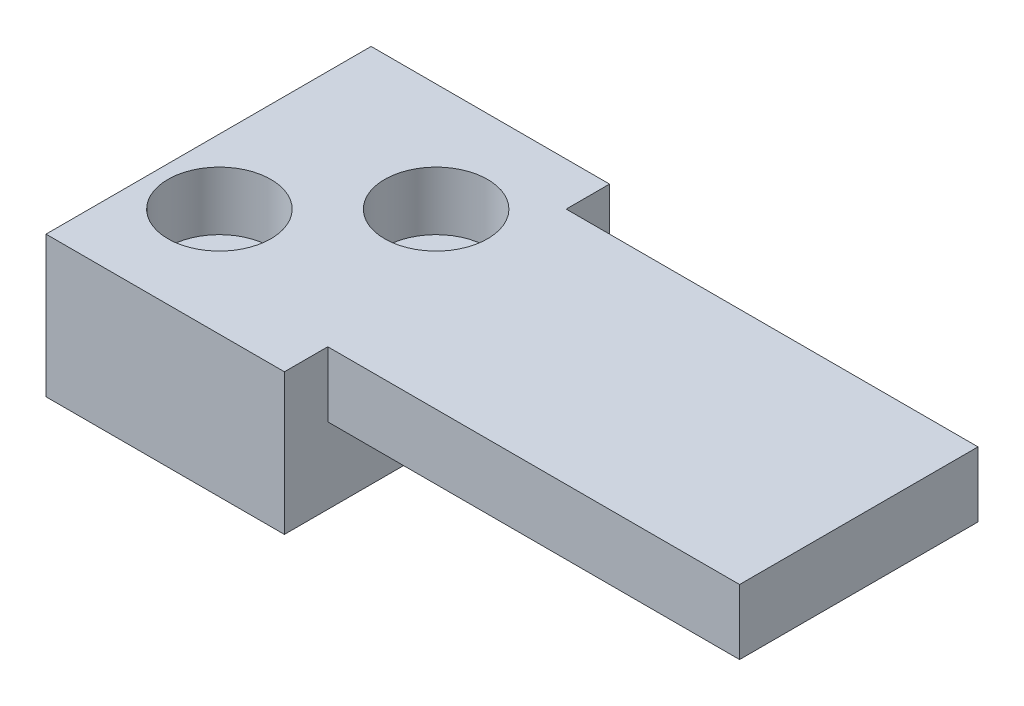
SolidWorks part; units mm, degrees
material "1.7131 (16MnCr5)"
ref_plane "Plano frontal" through (0, 0, 0) normal (0, 0, 1) x (1, 0, 0)
ref_plane "Plano superior" through (0, 0, 0) normal (0, 1, 0) x (1, 0, 0)
ref_plane "Plano direito" through (0, 0, 0) normal (1, 0, 0) x (0, 0, -1)
sketch "Esboço1" plane through (0, 0, 0) normal (0, 0, 1) x (1, 0, 0)
  line L0 (0, 0) -> (60, 0)
  line L1 (0, 0) -> (0, -13)
  line L2 (0, -13) -> (22, -13)
  line L3 (22, -13) -> (22, 0)
  line L4 (60, 0) -> (60, -6)
  line L5 (60, -6) -> (22, -6)
  dimension "D1" = 60
  dimension "D2" = 13
  dimension "D3" = 6
  dimension "D4" = 22
extrude "Ressalto-extrusão1" add sketch "Esboço1" along normal blind 30 contours L2 L3 L0 L1 | L5 L4 L0 L3
sketch "Esboço2" plane through (0, 0, 0) normal (0, 1, 0) x (1, 0, 0)
  line L0 (60, 0) -> (60, -4)
  line L1 (60, -30) -> (60, 0) construction
  line L2 (60, -30) -> (60, -26)
  line L3 (0, 0) -> (22, 0)
  line L4 (60, -4) -> (60, -26)
  line L5 (0, 0) -> (60, 0) construction
  line L6 (60, -4) -> (22, -4)
  line L7 (22, -4) -> (22, 0)
  line L8 (60, -26) -> (22, -26)
  line L9 (22, -26) -> (22, -30)
  line L10 (0, -30) -> (60, -30) construction
  line M4 (60, 0) -> (0, 0)
  line M6 (0, -30) -> (60, -30)
  line M7 (60, -30) -> (60, 0)
  dimension "D1" = 4
  dimension "D2" = 4
  dimension "D3" = 22
extrude "Corte-extrusão1" cut sketch "Esboço2" against normal through all both and the other way through all contours L7 L6 M7 M4 | L8 L9 M6 M7
sketch "Esboço4" plane through (0, 0, 0) normal (0, 1, 0) x (1, 0, 0)
  line L3 (0, -30) -> (0, 0) construction
  circle A1 centre (6, -20) radius 2.75
  circle A3 centre (16, -10) radius 2.75
  point P3 (0, -15)
  dimension "D1" = 5
  dimension "D6" = 5.5
  dimension "D8" = 5.5
  dimension "D2" = 5
  dimension "D3" = 16
  dimension "D4" = 6
extrude "Corte-extrusão2" cut sketch "Esboço4" against normal through all both and the other way through all contours A1 | A3
sketch "Esboço5" plane through (0, 0, 0) normal (0, 1, 0) x (1, 0, 0)
  circle A0 centre (6, -20) radius 4.75
  circle A1 centre (16, -10) radius 4.75
  dimension "D1" = 9.5
  dimension "D2" = 9.5
extrude "Corte-extrusão3" cut sketch "Esboço5" against normal blind 5.4
